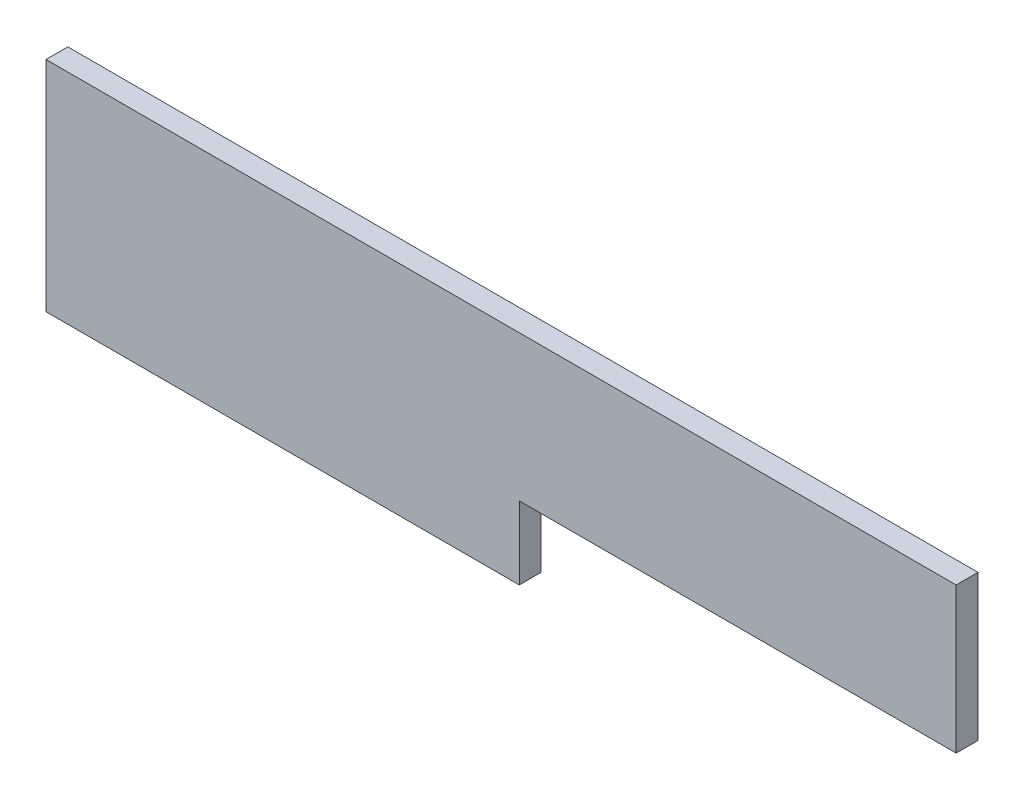
SolidWorks part; units mm, degrees
material "Сталь 3 ГОСТ 535-88"
ref_plane "Спереди" through (0, 0, 0) normal (0, 0, 1) x (1, 0, 0)
ref_plane "Сверху" through (0, 0, 0) normal (0, 1, 0) x (1, 0, 0)
ref_plane "Справа" through (0, 0, 0) normal (1, 0, 0) x (0, 0, -1)
sketch "Эскиз1" plane through (0, 0, 0) normal (0, 0, 1) x (1, 0, 0)
  line L0 (-65, 0) -> (-65, 60)
  line L1 (-65, 60) -> (185, 60)
  line L2 (185, 60) -> (185, 20)
  line L3 (185, 20) -> (65, 20)
  line L4 (65, 20) -> (65, 0)
  line L6 (65, 0) -> (-65, 0)
  point P6 (0, 0)
  point P8 (0, 0)
  point P9 (0, 0)
  point P10 (0, 0)
  point P11 (0, 0)
  point P12 (0, 0)
  point P13 (0, 0)
  point P15 (0, 0)
  point P16 (0, 0)
  point P17 (0, 0)
  point P18 (0, 0)
  point P19 (0, 0)
  point P20 (0, 0)
  point P21 (0, 0)
  dimension "D1" = 130
  dimension "D2" = 60
  dimension "D3" = 40
  dimension "D4" = 250
extrude "Бобышка-Вытянуть1" add sketch "Эскиз1" against normal blind 6
